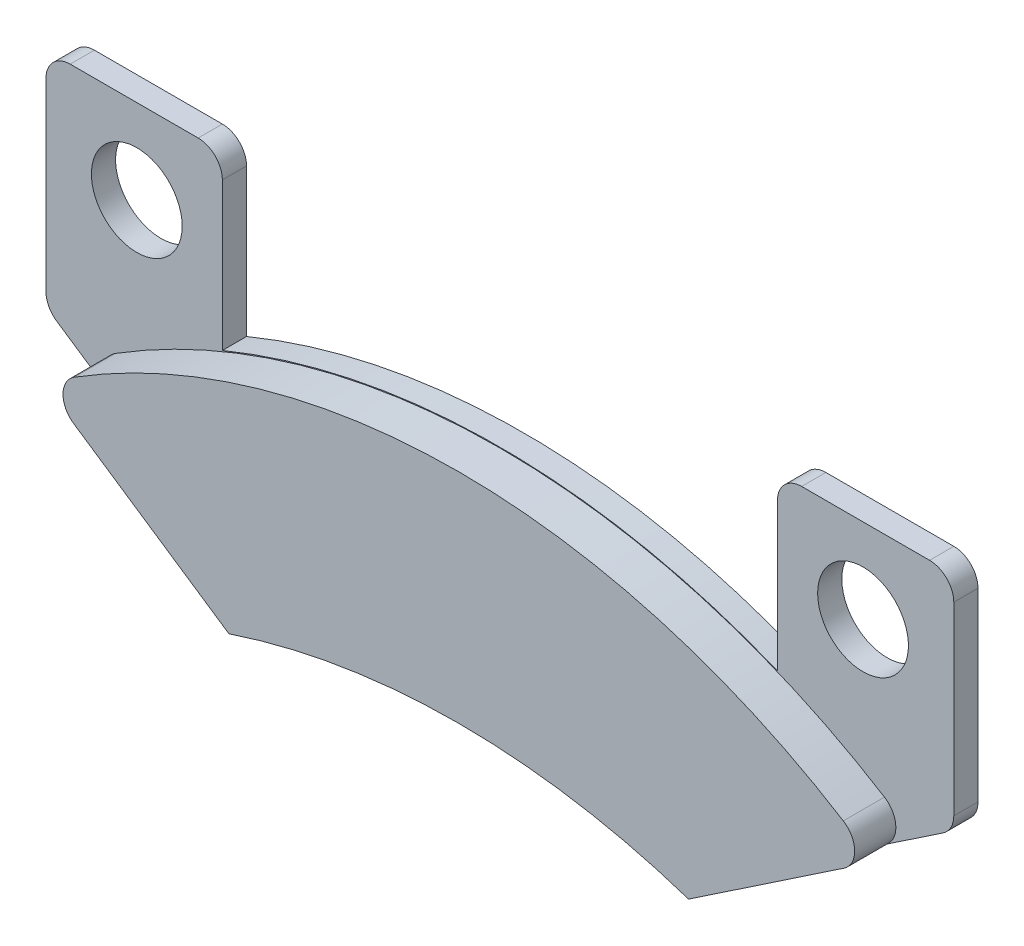
SolidWorks part; units mm, degrees
ref_plane "Front Plane" through (0, 0, 0) normal (0, 0, 1) x (1, 0, 0)
ref_plane "Top Plane" through (0, 0, 0) normal (0, 1, 0) x (1, 0, 0)
ref_plane "Right Plane" through (0, 0, 0) normal (1, 0, 0) x (0, 0, -1)
sketch "Sketch1" plane through (0, 0, 0) normal (0, 0, 1) x (1, 0, 0)
  line L0 (0, 45.8779) -> (0, -40.9218) construction
  line L1 (-29.1207, -1.1283) -> (-29.1207, 16.9068)
  line L2 (-29.1207, 16.9068) -> (-47.625, 16.9068)
  line L3 (-47.625, 16.9068) -> (-47.625, -6.402)
  line L4 (-47.625, -6.402) -> (-24.1149, -22.2092)
  line L5 (47.625, -6.402) -> (24.1149, -22.2092)
  line L6 (47.625, 16.9068) -> (47.625, -6.402)
  line L7 (29.1207, 16.9068) -> (47.625, 16.9068)
  line L8 (29.1207, -1.1283) -> (29.1207, 16.9068)
  arc A0 (29.1207, -1.1283) -> (-29.1207, -1.1283) centre (0, -71.5444) ccw
  arc A1 (-24.1149, -22.2092) -> (24.1149, -22.2092) centre (0, -94.4927) cw
  circle A2 centre (-38.1, 8.048) radius 4.7625
  circle A3 centre (38.1, 8.048) radius 4.7625
  dimension "D3" = 76.2
  dimension "D4" = 76.2
  dimension "D6" = 9.525
  dimension "D1" = 95.25
  dimension "D2" = 39.116
  dimension "D5" = 38.1
extrude "Boss-Extrude1" add sketch "Sketch1" along normal blind 2.54
sketch "Sketch2" plane through (0, 0, 2.54) normal (0, 0, 1) x (1, 0, 0)
  line L0 (-43.5603, -9.1349) -> (-24.1149, -22.2092)
  line L1 (24.1149, -22.2092) -> (43.5871, -9.1169)
  line L8 (24.1149, -22.2092) -> (47.625, -6.402) construction
  line L9 (-47.625, -6.402) -> (-24.1149, -22.2092) construction
  arc A1 (24.1149, -22.2092) -> (-24.1149, -22.2092) centre (0, -94.4927) ccw construction
  arc A2 (24.1149, -22.2092) -> (-24.1149, -22.2092) centre (0, -94.4927) ccw
  arc A3 (43.5871, -9.1169) -> (-43.5603, -9.1349) centre (0.0263, -71.5821) ccw
  arc A4 (29.1207, -1.1283) -> (-29.1207, -1.1283) centre (0, -71.5444) ccw construction
extrude "Boss-Extrude2" add sketch "Sketch2" along normal blind 4.318
fillet "Fillet1" radius 2.54 8 edges at (-47.625, -6.402, 1.27) (-47.625, 16.9068, 1.27) (-29.1207, 16.9068, 1.27) (47.625, -6.402, 1.27) (29.1207, 16.9068, 1.27) (47.625, 16.9068, 1.27) (-43.5603, -9.1349, 4.699) (43.5871, -9.1169, 4.699)
